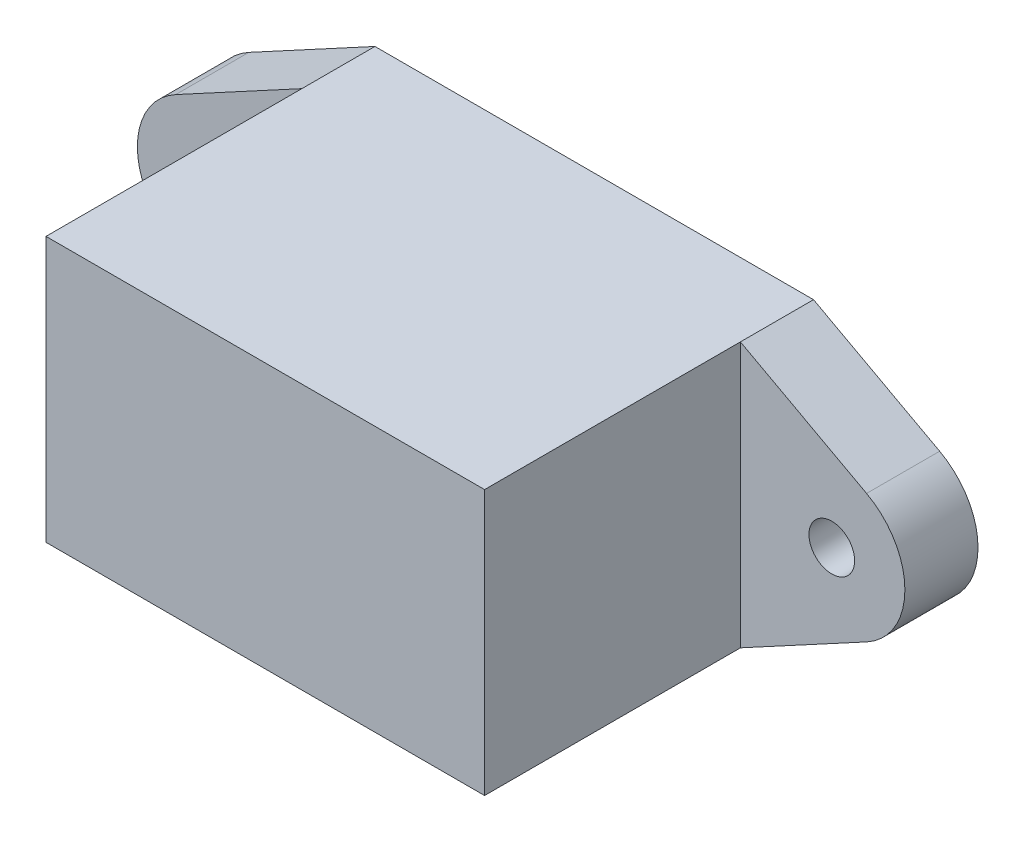
SolidWorks part; units mm, degrees
ref_plane "Спереди" through (0, 0, 0) normal (0, 0, 1) x (1, 0, 0)
ref_plane "Сверху" through (0, 0, 0) normal (0, 1, 0) x (1, 0, 0)
ref_plane "Справа" through (0, 0, 0) normal (1, 0, 0) x (0, 0, -1)
sketch "Эскиз1" plane through (0, 0, 0) normal (0, 0, 1) x (1, 0, 0)
  line L0 (0, 0) -> (-24, 0)
  line L1 (-24, 0) -> (-24, 14.5)
  line L2 (-24, 14.5) -> (0, 14.5)
  line L3 (0, 14.5) -> (0, 0)
extrude "Бобышка-Вытянуть1" add sketch "Эскиз1" along normal blind 18
sketch "Эскиз2" plane through (0, 0, 0) normal (0, 0, -1) x (-1, 0, 0)
  line L0 (-9, 7.25) -> (-5, 7.25) construction
  line L2 (24, 0) -> (0, 0) construction
  line L3 (12, 0) -> (12, 7.25) construction
  line L4 (-9, 7.25) -> (33, 7.25) construction
  line L5 (24, 14.5) -> (24, 0)
  line L6 (24, 14.5) -> (30.9022, 10.7688)
  line L7 (33, 7.25) -> (29, 7.25) construction
  line L8 (24, 0) -> (30.9022, 3.7312)
  line L9 (0, 0) -> (-6.9022, 3.7312)
  line L10 (0, 14.5) -> (-6.9022, 10.7688)
  line L11 (0, 14.5) -> (0, 0)
  circle A0 centre (29, 7.25) radius 1.25
  arc A1 (30.9022, 3.7312) -> (30.9022, 10.7688) centre (29, 7.25) ccw
  arc A2 (-6.9022, 3.7312) -> (-6.9022, 10.7688) centre (-5, 7.25) cw
  circle A3 centre (-5, 7.25) radius 1.25
  dimension "D1" = 21
extrude "Бобышка-Вытянуть2" add sketch "Эскиз2" against normal blind 4 separate body
sketch "Эскиз3" plane through (0, 0, 0) normal (0, 0, -1) x (-1, 0, 0)
  line L0 (24, 14.5) -> (0, 0) construction
  line L1 (0, 0) -> (0, 14.5) construction
  line L2 (0, 14.5) -> (24, 0) construction
  line L3 (12, 7.25) -> (19, 7.25) construction
  line L4 (12, 7.25) -> (5, 7.25) construction
  line L5 (12, 7.25) -> (12, 10.75) construction
  line L6 (12, 7.25) -> (12, 3.75) construction
  line L7 (5, 7.25) -> (5, 10.75)
  line L8 (5, 10.75) -> (19, 10.75)
  line L9 (19, 10.75) -> (19, 3.75)
  line L10 (19, 3.75) -> (5, 3.75)
  line L11 (5, 3.75) -> (5, 7.25)
extrude "Вырез-Вытянуть1" cut sketch "Эскиз3" against normal blind 1.5
